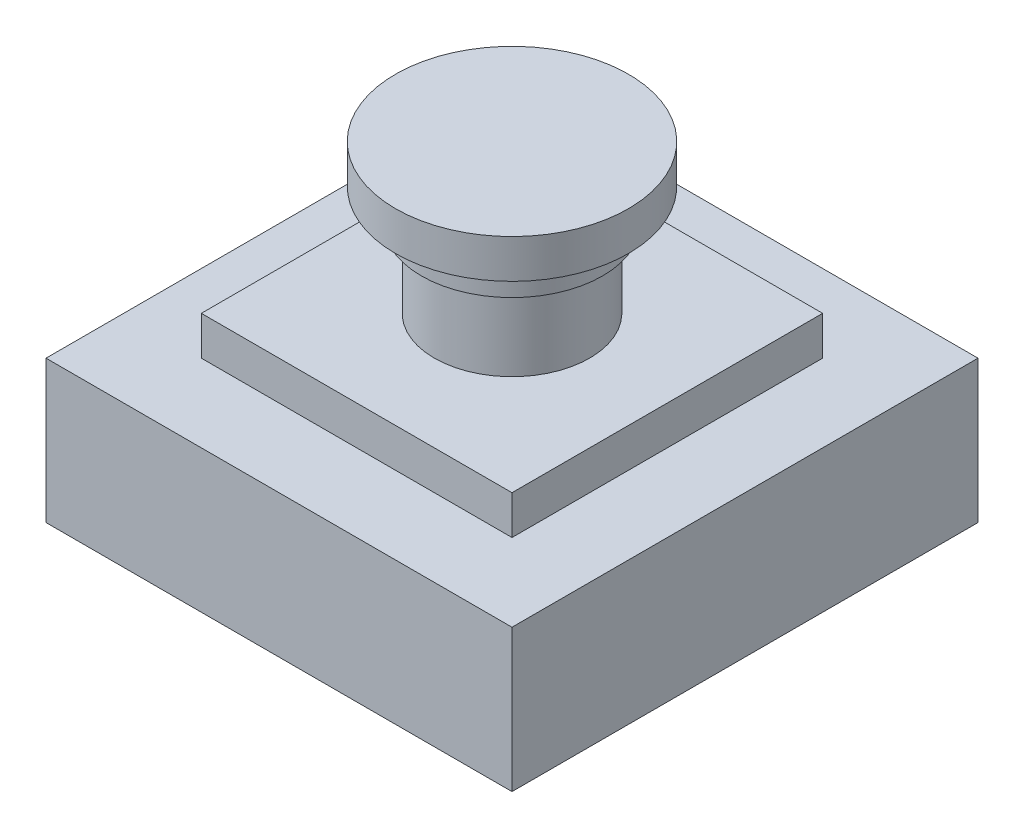
SolidWorks part; units mm, degrees
ref_plane "Front Plane" through (0, 0, 0) normal (0, 0, 1) x (1, 0, 0)
ref_plane "Top Plane" through (0, 0, 0) normal (0, 1, 0) x (1, 0, 0)
ref_plane "Right Plane" through (0, 0, 0) normal (1, 0, 0) x (0, 0, -1)
sketch "Sketch1" plane through (0, 0, 0) normal (0, 1, 0) x (1, 0, 0)
  line L1 (-18, 18) -> (18, 18)
  line L2 (-18, 18) -> (-18, -18)
  line L3 (-18, -18) -> (18, -18)
  line L4 (18, 18) -> (18, -18)
  line L5 (-18, 18) -> (18, -18) construction
  line L6 (-18, -18) -> (18, 18) construction
  point P0 (0, 0)
  dimension "D1" = 36
  dimension "D2" = 36
extrude "Boss-Extrude1" add sketch "Sketch1" along normal blind 11
sketch "Sketch2" plane through (0, 11, 0) normal (0, 1, 0) x (1, 0, 0)
  line L1 (-12, 12) -> (12, 12)
  line L2 (-12, 12) -> (-12, -12)
  line L3 (-12, -12) -> (12, -12)
  line L4 (12, 12) -> (12, -12)
  line L5 (-12, 12) -> (12, -12) construction
  line L6 (-12, -12) -> (12, 12) construction
  point P0 (0, 0)
  dimension "D1" = 24
  dimension "D2" = 24
extrude "Boss-Extrude2" add sketch "Sketch2" along normal blind 3
sketch "Sketch3" plane through (0, 14, 0) normal (0, 1, 0) x (1, 0, 0)
  circle A0 centre (0, 0) radius 6
extrude "Boss-Extrude3" add sketch "Sketch3" along normal blind 6
sketch "Sketch4" plane through (0, 20, 0) normal (0, 1, 0) x (1, 0, 0)
  circle A0 centre (0, 0) radius 7
extrude "Boss-Extrude4" add sketch "Sketch4" along normal blind 2.5
sketch "Sketch5" plane through (0, 22.5, 0) normal (0, 1, 0) x (1, 0, 0)
  circle A0 centre (0, 0) radius 9
extrude "Boss-Extrude5" add sketch "Sketch5" along normal blind 3
